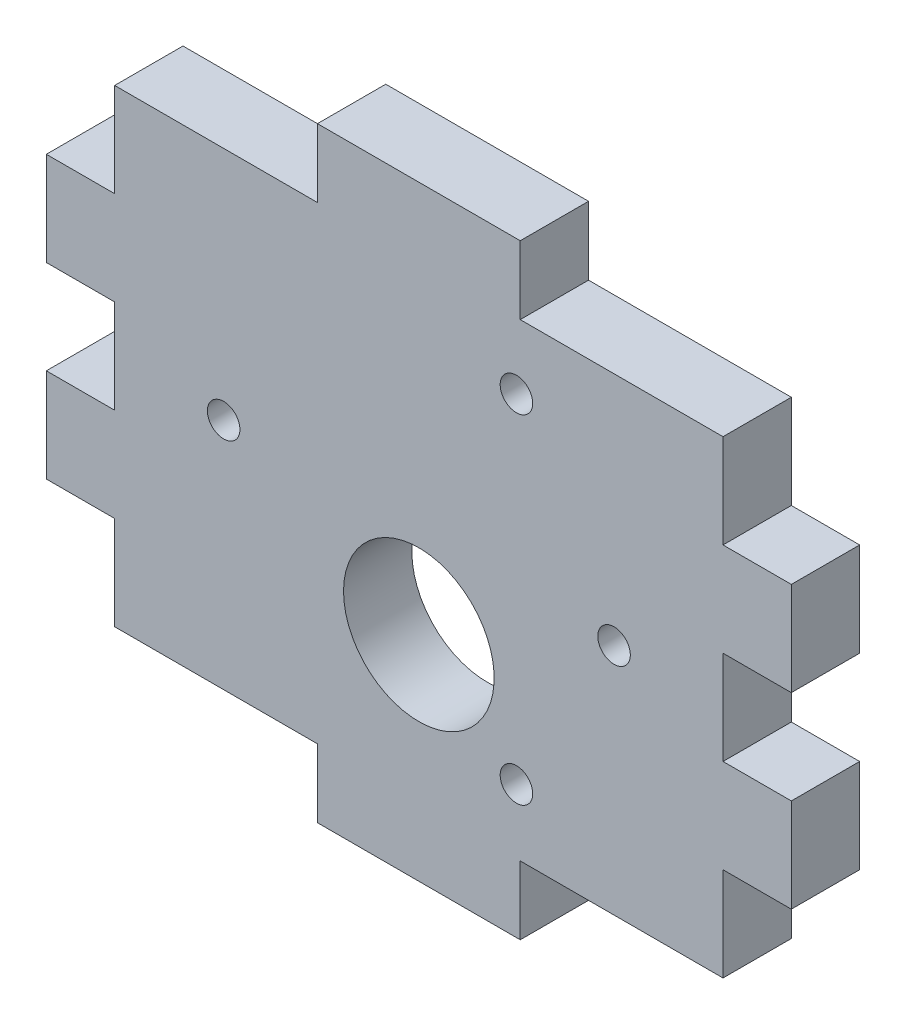
SolidWorks part; units mm, degrees
ref_plane "Front Plane" through (0, 0, 0) normal (0, 0, 1) x (1, 0, 0)
ref_plane "Top Plane" through (0, 0, 0) normal (0, 1, 0) x (1, 0, 0)
ref_plane "Right Plane" through (0, 0, 0) normal (1, 0, 0) x (0, 0, -1)
sketch "Sketch1" plane through (0, 0, 0) normal (0, 0, 1) x (1, 0, 0)
  line L1 (-23.749, -18.3007) -> (23.749, -18.3007)
  line L2 (-23.749, -18.3007) -> (-23.749, 18.3007)
  line L3 (-23.749, 18.3007) -> (23.749, 18.3007)
  line L4 (23.749, -18.3007) -> (23.749, 18.3007)
  line L5 (-23.749, -18.3007) -> (23.749, 18.3007) construction
  line L6 (-23.749, 18.3007) -> (23.749, -18.3007) construction
  point P0 (0, 0)
  dimension "D1" = 47.498
extrude "Boss-Extrude1" add sketch "Sketch1" along normal mid plane 5.334
sketch "Sketch3" plane through (0, 0, 2.667) normal (0, 0, 1) x (1, 0, 0)
  line L0 (-23.749, 18.3007) -> (-23.749, -18.3007) construction
  line L1 (-23.749, 10.9804) -> (-29.083, 10.9804)
  line L2 (-23.749, 10.9804) -> (-23.749, 3.6601)
  line L3 (-23.749, 3.6601) -> (-29.083, 3.6601)
  line L4 (-29.083, 10.9804) -> (-29.083, 3.6601)
  line L5 (-23.749, 10.9804) -> (-23.749, 18.3007) construction
  line L6 (-23.749, -10.9804) -> (-29.083, -10.9804)
  line L7 (-23.749, -10.9804) -> (-23.749, -3.6601)
  line L8 (-23.749, -3.6601) -> (-29.083, -3.6601)
  line L9 (-29.083, -10.9804) -> (-29.083, -3.6601)
  line L10 (-23.749, 3.6601) -> (-23.749, -3.6601) construction
  line L11 (-23.749, -10.9804) -> (-23.749, -18.3007) construction
  line L12 (0, 0) -> (0, 19.349) construction
  line L13 (23.749, -10.9804) -> (23.749, -18.3007) construction
  line L14 (23.749, -10.9804) -> (23.749, -18.3007) construction
  line L15 (23.749, 3.6601) -> (23.749, -3.6601) construction
  line L16 (23.749, 10.9804) -> (23.749, 18.3007) construction
  line L17 (29.083, -10.9804) -> (29.083, -3.6601)
  line L18 (23.749, -3.6601) -> (29.083, -3.6601)
  line L19 (23.749, -10.9804) -> (23.749, -3.6601)
  line L20 (23.749, -10.9804) -> (29.083, -10.9804)
  line L21 (29.083, 10.9804) -> (29.083, 3.6601)
  line L22 (23.749, 3.6601) -> (29.083, 3.6601)
  line L23 (23.749, 10.9804) -> (23.749, 3.6601)
  line L24 (23.749, 10.9804) -> (29.083, 10.9804)
extrude "Boss-Extrude3" add sketch "Sketch3" against normal blind 5.334
sketch "Sketch5" plane through (0, 0, 2.667) normal (0, 0, 1) x (1, 0, 0)
  line L0 (-23.749, -18.3007) -> (23.749, -18.3007) construction
  line L1 (-7.9163, -18.3007) -> (7.9163, -18.3007)
  line L2 (-7.9163, -18.3007) -> (-7.9163, -23.6347)
  line L3 (-7.9163, -23.6347) -> (7.9163, -23.6347)
  line L4 (7.9163, -18.3007) -> (7.9163, -23.6347)
  line L5 (-23.749, -18.3007) -> (-7.9163, -18.3007) construction
  line L6 (-23.749, -10.9804) -> (-23.749, -18.3007) construction
  line L7 (7.9163, -18.3007) -> (23.749, -18.3007) construction
  line L8 (0, 0) -> (39.0938, 0) construction
  line L9 (7.9163, 18.3007) -> (7.9163, 23.6347)
  line L10 (-7.9163, 23.6347) -> (7.9163, 23.6347)
  line L11 (-7.9163, 18.3007) -> (-7.9163, 23.6347)
  line L12 (-7.9163, 18.3007) -> (7.9163, 18.3007)
extrude "Boss-Extrude4" add sketch "Sketch5" against normal blind 5.334
sketch "Sketch6" plane through (0, 0, -2.667) normal (0, 0, -1) x (-1, 0, 0)
  line L28 (-23.749, -10.9804) -> (-23.749, -18.3007)
  line L29 (-23.749, -18.3007) -> (-7.9163, -18.3007)
  line L30 (-7.9163, -18.3007) -> (-7.9163, -23.6347)
  line L31 (-7.9163, -23.6347) -> (7.9163, -23.6347)
  line L32 (7.9163, -23.6347) -> (7.9163, -18.3007)
  line L33 (7.9163, -18.3007) -> (23.749, -18.3007)
  line L34 (23.749, -18.3007) -> (23.749, -10.9804)
  line L35 (23.749, -10.9804) -> (29.083, -10.9804)
  line L36 (29.083, -10.9804) -> (29.083, -3.6601)
  line L37 (29.083, -3.6601) -> (23.749, -3.6601)
  line L38 (23.749, -3.6601) -> (23.749, 3.6601)
  line L39 (23.749, 3.6601) -> (29.083, 3.6601)
  line L40 (29.083, 3.6601) -> (29.083, 10.9804)
  line L41 (29.083, 10.9804) -> (23.749, 10.9804)
  line L42 (23.749, 10.9804) -> (23.749, 18.3007)
  line L43 (23.749, 18.3007) -> (7.9163, 18.3007)
  line L44 (7.9163, 18.3007) -> (7.9163, 23.6347)
  line L45 (7.9163, 23.6347) -> (-7.9163, 23.6347)
  line L46 (-7.9163, 23.6347) -> (-7.9163, 18.3007)
  line L47 (-7.9163, 18.3007) -> (-23.749, 18.3007)
  line L48 (-23.749, 18.3007) -> (-23.749, 10.9804)
  line L49 (-23.749, 10.9804) -> (-29.083, 10.9804)
  line L50 (-29.083, 10.9804) -> (-29.083, 3.6601)
  line L51 (-29.083, 3.6601) -> (-23.749, 3.6601)
  line L52 (-23.749, 3.6601) -> (-23.749, -3.6601)
  line L53 (-23.749, -3.6601) -> (-29.083, -3.6601)
  line L54 (-29.083, -3.6601) -> (-29.083, -10.9804)
  line L55 (-29.083, -10.9804) -> (-23.749, -10.9804)
  line L56 (-23.749, -10.9804) -> (-23.749, -18.3007)
  line L57 (-23.749, -18.3007) -> (-7.9163, -18.3007)
  line L58 (-7.9163, -18.3007) -> (-7.9163, -23.6347)
  line L59 (-7.9163, -23.6347) -> (7.9163, -23.6347)
  line L60 (7.9163, -23.6347) -> (7.9163, -18.3007)
  line L61 (7.9163, -18.3007) -> (23.749, -18.3007)
  line L62 (23.749, -18.3007) -> (23.749, -10.9804)
  line L63 (23.749, -10.9804) -> (29.083, -10.9804)
  line L64 (29.083, -10.9804) -> (29.083, -3.6601)
  line L65 (29.083, -3.6601) -> (23.749, -3.6601)
  line L66 (23.749, -3.6601) -> (23.749, 3.6601)
  line L67 (23.749, 3.6601) -> (29.083, 3.6601)
  line L68 (29.083, 3.6601) -> (29.083, 10.9804)
  line L69 (29.083, 10.9804) -> (23.749, 10.9804)
  line L70 (23.749, 10.9804) -> (23.749, 18.3007)
  line L71 (23.749, 18.3007) -> (7.9163, 18.3007)
  line L72 (7.9163, 18.3007) -> (7.9163, 23.6347)
  line L73 (7.9163, 23.6347) -> (-7.9163, 23.6347)
  line L74 (-7.9163, 23.6347) -> (-7.9163, 18.3007)
  line L75 (-7.9163, 18.3007) -> (-23.749, 18.3007)
  line L76 (-23.749, 18.3007) -> (-23.749, 10.9804)
  line L77 (-23.749, 10.9804) -> (-29.083, 10.9804)
  line L78 (-29.083, 10.9804) -> (-29.083, 3.6601)
  line L79 (-29.083, 3.6601) -> (-23.749, 3.6601)
  line L80 (-23.749, 3.6601) -> (-23.749, -3.6601)
  line L81 (-23.749, -3.6601) -> (-29.083, -3.6601)
  line L82 (-29.083, -3.6601) -> (-29.083, -10.9804)
  line L83 (-29.083, -10.9804) -> (-23.749, -10.9804)
  circle A0 centre (-15.24, -0.0762) radius 1.27 construction
  circle A1 centre (-7.62, -13.2744) radius 1.27 construction
  circle A2 centre (15.24, -0.0762) radius 1.27 construction
  circle A3 centre (-7.62, 13.122) radius 1.27 construction
  circle A4 centre (-15.24, -0.0762) radius 1.27
  circle A5 centre (-7.62, -13.2744) radius 1.27
  circle A6 centre (15.24, -0.0762) radius 1.27
  circle A7 centre (-7.62, 13.122) radius 1.27
  circle A8 centre (0, -6.9596) radius 5.8801 construction
  circle A9 centre (0, -6.9596) radius 5.8801
  dimension "D1" = 0
extrude "Cut-Extrude1" cut sketch "Sketch6" against normal through all contours A6 | A9 | A5 | A7 | A4
equation "\"height\"=1.441"
equation "\"material\"=\"GMaterial@MotorizedPlatform.assembly\""
equation "\"D1@Boss-Extrude1\"=\"material\""
equation "\"D1@Boss-Extrude3\" = \"material\""
equation "\"D1@Boss-Extrude4\" = \"material\""
